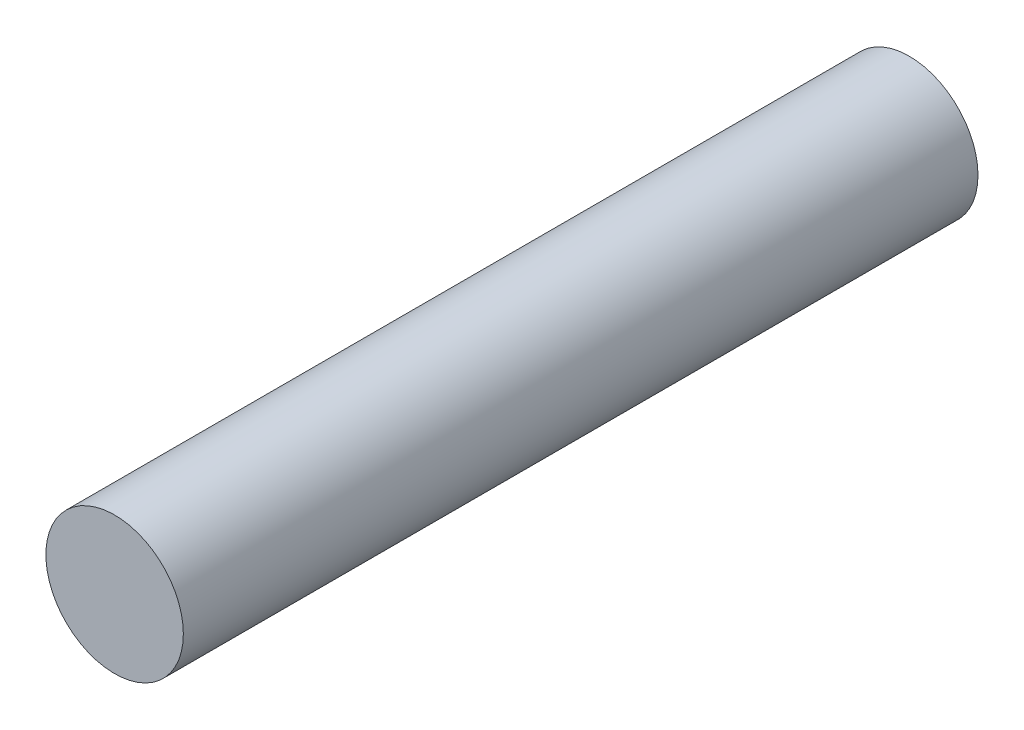
SolidWorks part; units mm, degrees
material "7075-T6 (SN)"
ref_plane "前视基准面" through (0, 0, 0) normal (0, 0, 1) x (1, 0, 0)
ref_plane "上视基准面" through (0, 0, 0) normal (0, 1, 0) x (1, 0, 0)
ref_plane "右视基准面" through (0, 0, 0) normal (1, 0, 0) x (0, 0, -1)
sketch "草图1" plane through (0, 0, 0) normal (0, 0, 1) x (1, 0, 0)
  circle A0 centre (-39.8906, 50.7386) radius 4.0654
extrude "凸台-拉伸1" add sketch "草图1" against normal blind 38 and the other way blind 9
